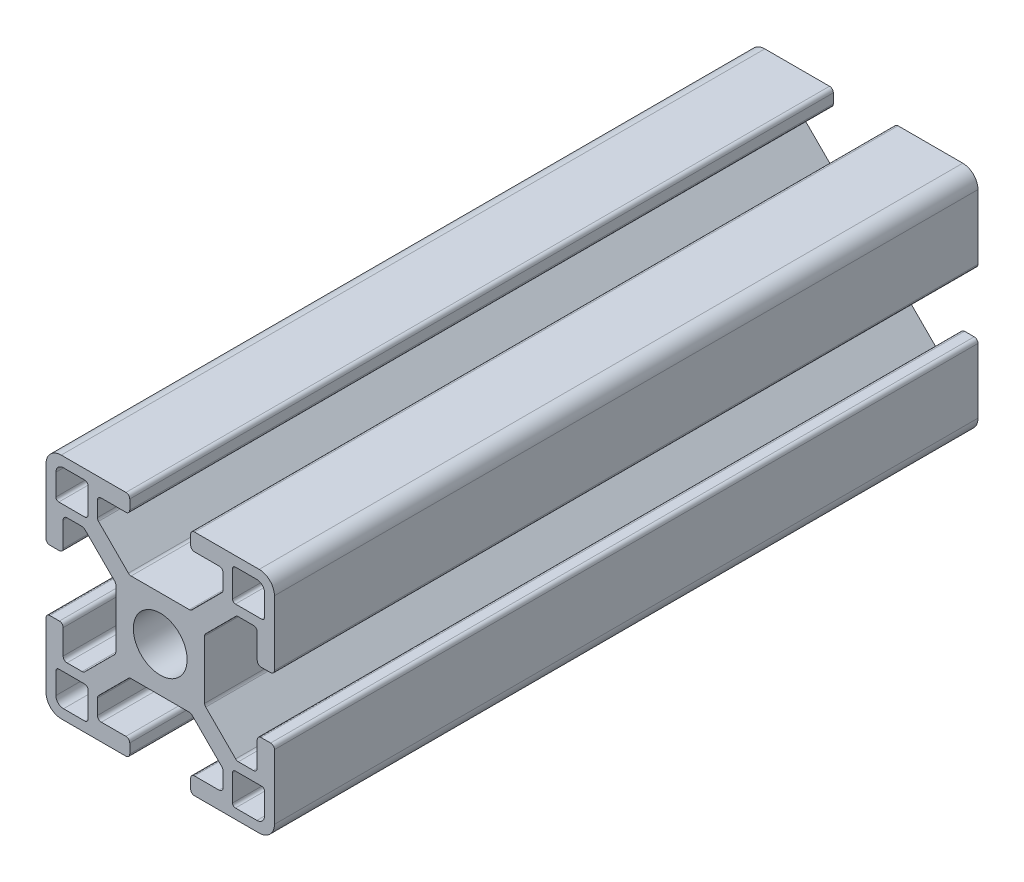
SolidWorks part; units mm, degrees
ref_plane "Front Plane" through (0, 0, 0) normal (0, 0, 1) x (1, 0, 0)
ref_plane "Top Plane" through (0, 0, 0) normal (0, 1, 0) x (1, 0, 0)
ref_plane "Right Plane" through (0, 0, 0) normal (1, 0, 0) x (0, 0, -1)
sketch "Sketch1" plane through (0, 0, 0) normal (0, 0, 1) x (1, 0, 0)
  line L0 (3.9799, -2.4733) -> (3.1981, -1.4942) construction
  line L1 (1.4942, -3.1981) -> (2.4733, -3.9799) construction
  line L2 (-2.4733, -3.9799) -> (-1.4942, -3.1981) construction
  line L3 (-3.1981, -1.4942) -> (-3.9799, -2.4733) construction
  line L4 (-3.9799, 2.4733) -> (-3.1981, 1.4942) construction
  line L5 (-1.4942, 3.1981) -> (-2.4733, 3.9799) construction
  line L6 (2.4733, 3.9799) -> (1.4942, 3.1981) construction
  line L7 (3.1981, 1.4942) -> (3.9799, 2.4733) construction
  line L8 (-12.6999, -13.6999) -> (-9.881, -13.6999)
  line L9 (-13.6999, -9.881) -> (-13.6999, -12.6999)
  line L10 (-9.88, -9.5) -> (-13.3189, -9.5)
  line L11 (-9.5, -13.3189) -> (-9.5, -9.88)
  line L12 (13.6999, -12.6999) -> (13.6999, -9.881)
  line L13 (9.881, -13.6999) -> (12.6999, -13.6999)
  line L14 (9.5, -9.88) -> (9.5, -13.3189)
  line L15 (13.3189, -9.5) -> (9.88, -9.5)
  line L16 (9.88, 9.5) -> (13.3189, 9.5)
  line L17 (9.5, 13.3189) -> (9.5, 9.88)
  line L18 (12.6999, 13.6999) -> (9.881, 13.6999)
  line L19 (13.6999, 9.881) -> (13.6999, 12.6999)
  line L20 (-13.6999, 12.6999) -> (-13.6999, 9.881)
  line L21 (-9.881, 13.6999) -> (-12.6999, 13.6999)
  line L22 (-9.5, 9.88) -> (-9.5, 13.3189)
  line L23 (-13.3189, 9.5) -> (-9.88, 9.5)
  line L24 (14.4999, -4) -> (13.2425, -4)
  line L25 (12.7425, -4.5) -> (12.7425, -7.7325)
  line L26 (12.2428, -8.25) -> (10.2602, -8.25)
  line L27 (9.9066, -8.1035) -> (5.9811, -4.178)
  line L28 (5.8347, -3.8245) -> (5.8347, -1.0125)
  line L29 (5.8347, -1.0125) -> (5.3247, -0.0625) construction
  line L30 (5.3247, -0.0625) -> (5.8347, 0.8875) construction
  line L31 (5.8347, 0.8875) -> (5.8347, 3.8245)
  line L32 (5.9811, 4.178) -> (9.9066, 8.1035)
  line L33 (10.2602, 8.25) -> (12.2428, 8.25)
  line L34 (12.7425, 7.7325) -> (12.7425, 4.5)
  line L35 (13.2425, 4) -> (14.4999, 4)
  line L36 (14.9999, 4.5) -> (14.9999, 12.9999)
  line L37 (12.9999, 14.9999) -> (4.5, 14.9999)
  line L38 (4, 14.4999) -> (4, 13.2425)
  line L39 (4.5, 12.7425) -> (7.7325, 12.7425)
  line L40 (8.25, 12.2428) -> (8.25, 10.2602)
  line L41 (8.1035, 9.9066) -> (4.178, 5.9811)
  line L42 (3.8245, 5.8347) -> (0.95, 5.8347)
  line L43 (0.95, 5.8347) -> (0, 5.3247) construction
  line L44 (0, 5.3247) -> (-0.95, 5.8347) construction
  line L45 (-0.95, 5.8347) -> (-3.8245, 5.8347)
  line L46 (-4.178, 5.9811) -> (-8.1035, 9.9066)
  line L47 (-8.25, 10.2602) -> (-8.25, 12.2428)
  line L48 (-7.7325, 12.7425) -> (-4.5, 12.7425)
  line L49 (-4, 13.2425) -> (-4, 14.4999)
  line L50 (-4.5, 14.9999) -> (-12.9999, 14.9999)
  line L51 (-14.9999, 12.9999) -> (-14.9999, 4.5)
  line L52 (-14.4999, 4) -> (-13.2425, 4)
  line L53 (-12.7425, 4.5) -> (-12.7425, 7.7325)
  line L54 (-12.2428, 8.25) -> (-10.2602, 8.25)
  line L55 (-9.9066, 8.1035) -> (-5.9811, 4.178)
  line L56 (-5.8347, 3.8245) -> (-5.8347, 0.8875)
  line L57 (-5.8347, 0.8875) -> (-5.3247, -0.0625) construction
  line L58 (-5.3247, -0.0625) -> (-5.8347, -1.0125) construction
  line L59 (-5.8347, -1.0125) -> (-5.8347, -3.8245)
  line L60 (-5.9811, -4.178) -> (-9.9066, -8.1035)
  line L61 (-10.2602, -8.25) -> (-12.2428, -8.25)
  line L62 (-12.7425, -7.7325) -> (-12.7425, -4.5)
  line L63 (-13.2425, -4) -> (-14.4999, -4)
  line L64 (-14.9999, -4.5) -> (-14.9999, -12.9999)
  line L65 (-12.9999, -14.9999) -> (-4.5, -14.9999)
  line L66 (-4, -14.4999) -> (-4, -13.2425)
  line L67 (-4.5, -12.7425) -> (-7.7325, -12.7425)
  line L68 (-8.25, -12.2428) -> (-8.25, -10.2602)
  line L69 (-8.1035, -9.9066) -> (-4.178, -5.9811)
  line L70 (-3.8245, -5.8347) -> (-0.95, -5.8347)
  line L71 (-0.95, -5.8347) -> (0, -5.3247) construction
  line L72 (0, -5.3247) -> (0.95, -5.8347) construction
  line L73 (0.95, -5.8347) -> (3.8245, -5.8347)
  line L74 (4.178, -5.9811) -> (8.1035, -9.9066)
  line L75 (8.25, -10.2602) -> (8.25, -12.2428)
  line L76 (7.7325, -12.7425) -> (4.5, -12.7425)
  line L77 (4, -13.2425) -> (4, -14.4999)
  line L78 (4.5, -14.9999) -> (12.9999, -14.9999)
  line L79 (14.9999, -12.9999) -> (14.9999, -4.5)
  line L80 (-5.8347, -1.0125) -> (-5.8347, 0.8875)
  line L81 (-0.95, 5.8347) -> (0.95, 5.8347)
  line L82 (5.8347, 0.8875) -> (5.8347, -1.0125)
  line L83 (-0.95, -5.8347) -> (0.95, -5.8347)
  arc A0 (2.4733, -3.9799) -> (3.9799, -2.4733) centre (3.1422, -3.1422) ccw construction
  arc A1 (-1.4942, -3.1981) -> (1.4942, -3.1981) centre (0, 0) ccw construction
  arc A2 (-3.9799, -2.4733) -> (-2.4733, -3.9799) centre (-3.1422, -3.1422) ccw construction
  arc A3 (-3.1981, 1.4942) -> (-3.1981, -1.4942) centre (0, 0) ccw construction
  arc A4 (-2.4733, 3.9799) -> (-3.9799, 2.4733) centre (-3.1422, 3.1422) ccw construction
  arc A5 (1.4942, 3.1981) -> (-1.4942, 3.1981) centre (0, 0) ccw construction
  arc A6 (3.9799, 2.4733) -> (2.4733, 3.9799) centre (3.1422, 3.1422) ccw construction
  arc A7 (3.1981, -1.4942) -> (3.1981, 1.4942) centre (0, 0) ccw construction
  arc A8 (-13.6999, -12.6999) -> (-12.6999, -13.6999) centre (-12.6999, -12.6999) ccw
  arc A9 (-13.3189, -9.5) -> (-13.6999, -9.881) centre (-13.3189, -9.881) ccw
  arc A10 (-9.5, -9.88) -> (-9.88, -9.5) centre (-9.88, -9.88) ccw
  arc A11 (-9.881, -13.6999) -> (-9.5, -13.3189) centre (-9.881, -13.3189) ccw
  arc A12 (12.6999, -13.6999) -> (13.6999, -12.6999) centre (12.6999, -12.6999) ccw
  arc A13 (9.5, -13.3189) -> (9.881, -13.6999) centre (9.881, -13.3189) ccw
  arc A14 (9.88, -9.5) -> (9.5, -9.88) centre (9.88, -9.88) ccw
  arc A15 (13.6999, -9.881) -> (13.3189, -9.5) centre (13.3189, -9.881) ccw
  arc A16 (9.5, 9.88) -> (9.88, 9.5) centre (9.88, 9.88) ccw
  arc A17 (9.881, 13.6999) -> (9.5, 13.3189) centre (9.881, 13.3189) ccw
  arc A18 (13.6999, 12.6999) -> (12.6999, 13.6999) centre (12.6999, 12.6999) ccw
  arc A19 (13.3189, 9.5) -> (13.6999, 9.881) centre (13.3189, 9.881) ccw
  arc A20 (14.9999, -4.5) -> (14.4999, -4) centre (14.4999, -4.5) ccw
  arc A21 (13.2425, -4) -> (12.7425, -4.5) centre (13.2425, -4.5) ccw
  arc A22 (12.2428, -8.25) -> (12.7425, -7.7325) centre (12.2428, -7.75) ccw
  arc A23 (9.9066, -8.1035) -> (10.2602, -8.25) centre (10.2602, -7.75) ccw
  arc A24 (5.8347, -3.8245) -> (5.9811, -4.178) centre (6.3347, -3.8245) ccw
  arc A25 (5.9811, 4.178) -> (5.8347, 3.8245) centre (6.3347, 3.8245) ccw
  arc A26 (10.2602, 8.25) -> (9.9066, 8.1035) centre (10.2602, 7.75) ccw
  arc A27 (12.7425, 7.7325) -> (12.2428, 8.25) centre (12.2428, 7.75) ccw
  arc A28 (12.7425, 4.5) -> (13.2425, 4) centre (13.2425, 4.5) ccw
  arc A29 (14.4999, 4) -> (14.9999, 4.5) centre (14.4999, 4.5) ccw
  arc A30 (14.9999, 12.9999) -> (12.9999, 14.9999) centre (12.9999, 12.9999) ccw
  arc A31 (4.5, 14.9999) -> (4, 14.4999) centre (4.5, 14.4999) ccw
  arc A32 (4, 13.2425) -> (4.5, 12.7425) centre (4.5, 13.2425) ccw
  arc A33 (8.25, 12.2428) -> (7.7325, 12.7425) centre (7.75, 12.2428) ccw
  arc A34 (8.1035, 9.9066) -> (8.25, 10.2602) centre (7.75, 10.2602) ccw
  arc A35 (3.8245, 5.8347) -> (4.178, 5.9811) centre (3.8245, 6.3347) ccw
  arc A36 (-4.178, 5.9811) -> (-3.8245, 5.8347) centre (-3.8245, 6.3347) ccw
  arc A37 (-8.25, 10.2602) -> (-8.1035, 9.9066) centre (-7.75, 10.2602) ccw
  arc A38 (-7.7325, 12.7425) -> (-8.25, 12.2428) centre (-7.75, 12.2428) ccw
  arc A39 (-4.5, 12.7425) -> (-4, 13.2425) centre (-4.5, 13.2425) ccw
  arc A40 (-4, 14.4999) -> (-4.5, 14.9999) centre (-4.5, 14.4999) ccw
  arc A41 (-12.9999, 14.9999) -> (-14.9999, 12.9999) centre (-12.9999, 12.9999) ccw
  arc A42 (-14.9999, 4.5) -> (-14.4999, 4) centre (-14.4999, 4.5) ccw
  arc A43 (-13.2425, 4) -> (-12.7425, 4.5) centre (-13.2425, 4.5) ccw
  arc A44 (-12.2428, 8.25) -> (-12.7425, 7.7325) centre (-12.2428, 7.75) ccw
  arc A45 (-9.9066, 8.1035) -> (-10.2602, 8.25) centre (-10.2602, 7.75) ccw
  arc A46 (-5.8347, 3.8245) -> (-5.9811, 4.178) centre (-6.3347, 3.8245) ccw
  arc A47 (-5.9811, -4.178) -> (-5.8347, -3.8245) centre (-6.3347, -3.8245) ccw
  arc A48 (-10.2602, -8.25) -> (-9.9066, -8.1035) centre (-10.2602, -7.75) ccw
  arc A49 (-12.7425, -7.7325) -> (-12.2428, -8.25) centre (-12.2428, -7.75) ccw
  arc A50 (-12.7425, -4.5) -> (-13.2425, -4) centre (-13.2425, -4.5) ccw
  arc A51 (-14.4999, -4) -> (-14.9999, -4.5) centre (-14.4999, -4.5) ccw
  arc A52 (-14.9999, -12.9999) -> (-12.9999, -14.9999) centre (-12.9999, -12.9999) ccw
  arc A53 (-4.5, -14.9999) -> (-4, -14.4999) centre (-4.5, -14.4999) ccw
  arc A54 (-4, -13.2425) -> (-4.5, -12.7425) centre (-4.5, -13.2425) ccw
  arc A55 (-8.25, -12.2428) -> (-7.7325, -12.7425) centre (-7.75, -12.2428) ccw
  arc A56 (-8.1035, -9.9066) -> (-8.25, -10.2602) centre (-7.75, -10.2602) ccw
  arc A57 (-3.8245, -5.8347) -> (-4.178, -5.9811) centre (-3.8245, -6.3347) ccw
  arc A58 (4.178, -5.9811) -> (3.8245, -5.8347) centre (3.8245, -6.3347) ccw
  arc A59 (8.25, -10.2602) -> (8.1035, -9.9066) centre (7.75, -10.2602) ccw
  arc A60 (7.7325, -12.7425) -> (8.25, -12.2428) centre (7.75, -12.2428) ccw
  arc A61 (4.5, -12.7425) -> (4, -13.2425) centre (4.5, -13.2425) ccw
  arc A62 (4, -14.4999) -> (4.5, -14.9999) centre (4.5, -14.4999) ccw
  arc A63 (12.9999, -14.9999) -> (14.9999, -12.9999) centre (12.9999, -12.9999) ccw
  arc A64 (-12.6999, 13.6999) -> (-13.6999, 12.6999) centre (-12.6999, 12.6999) ccw
  arc A65 (-9.5, 13.3189) -> (-9.881, 13.6999) centre (-9.881, 13.3189) ccw
  arc A66 (-9.88, 9.5) -> (-9.5, 9.88) centre (-9.88, 9.88) ccw
  arc A67 (-13.6999, 9.881) -> (-13.3189, 9.5) centre (-13.3189, 9.881) ccw
  circle A68 centre (0, 0) radius 3.53
extrude "Boss-Extrude1" add sketch "Sketch1" along normal mid plane 92.4
